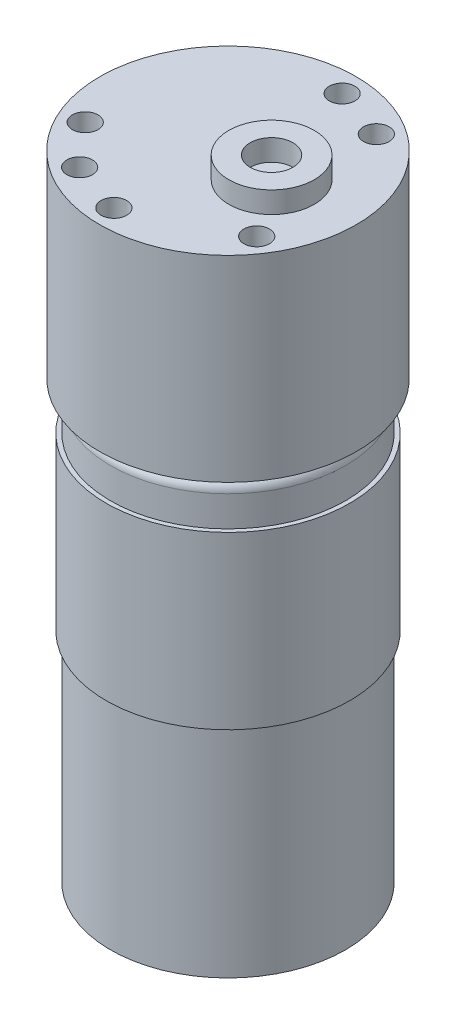
SolidWorks part; units mm, degrees
ref_plane "Piano frontale" through (0, 0, 0) normal (0, 0, 1) x (1, 0, 0)
ref_plane "Piano superiore" through (0, 0, 0) normal (0, 1, 0) x (1, 0, 0)
ref_plane "Piano destro" through (0, 0, 0) normal (1, 0, 0) x (0, 0, -1)
sketch "Sketch1" plane through (0, 0, 0) normal (0, 0, 1) x (1, 0, 0)
  line L0 (59.4956, 0) -> (-83.7363, 0) construction
  line L1 (33.7013, 0) -> (33.7013, 13.75)
  line L2 (33.7013, 13.75) -> (21.2013, 13.75)
  line L3 (-11.7987, 13.75) -> (-11.7987, 14.25)
  line L4 (21.2013, 13.75) -> (8.2013, 13.75)
  line L5 (-17.3987, 15.0046) -> (-17.3987, 12.5)
  line L6 (8.2013, 14.25) -> (8.2013, 13.75)
  line L7 (8.2013, 14.25) -> (-11.7987, 14.25)
  line L8 (33.7013, 0) -> (-40.3987, 0)
  line L9 (-16.5987, 12.5) -> (-16.5987, 12.51)
  line L11 (-40.3987, 0) -> (-40.3987, 15.0046)
  line L13 (-17.3987, 15.0046) -> (-40.3987, 15.0046)
  line L14 (-16.5987, 12.5) -> (-17.3987, 12.5)
  line L15 (-15.3587, 13.75) -> (-11.7987, 13.75)
  arc A0 (-16.5987, 12.51) -> (-15.3587, 13.75) centre (-15.3587, 12.51) cw
  dimension "D1" = 1.24
revolve "Revolve1" add sketch "Sketch1" angle 360 about L0
sketch "Sketch5" plane through (-40.3987, 0, 0) normal (-1, 0, 0) x (0, 0, 1)
  circle A0 centre (-12.5, 0) radius 1.5
  circle A1 centre (-10.8253, 6.25) radius 1.5
  circle A2 centre (6.25, 10.8253) radius 1.5
  circle A3 centre (12.5, 0) radius 1.5
  circle A4 centre (10.8253, -6.25) radius 1.5
  circle A5 centre (6.25, -10.8253) radius 1.5
extrude "Cut-Extrude1" cut sketch "Sketch5" against normal blind 4
sketch "Sketch3" plane through (-40.3987, 0, 0) normal (-1, 0, 0) x (0, 0, 1)
  circle A0 centre (0, 5.5) radius 5
  circle A1 centre (0, 5.5) radius 2.5
extrude "Boss-Extrude3" add sketch "Sketch3" along normal blind 2.5
move or copy body "Body-Move/Copy1" bodies to move or copy 104 copy no rotation origin (-4.5987, 0, 0) rotation axis (0, 0, 1) rotation angle 180
move or copy body "Body-Move/Copy2" bodies to move or copy 108 copy no rotation origin (-4.5987, 0, 0) rotation axis (0, -0.0354, 0.9994) rotation angle 180
move or copy body "Body-Move/Copy3" bodies to move or copy 109 copy no rotation origin (-4.5987, 0, 0) rotation axis (0, 0, -1) rotation angle 90
move or copy body "Body-Move/Copy4" bodies to move or copy 110 copy no translate (74.015, 0, 0)
